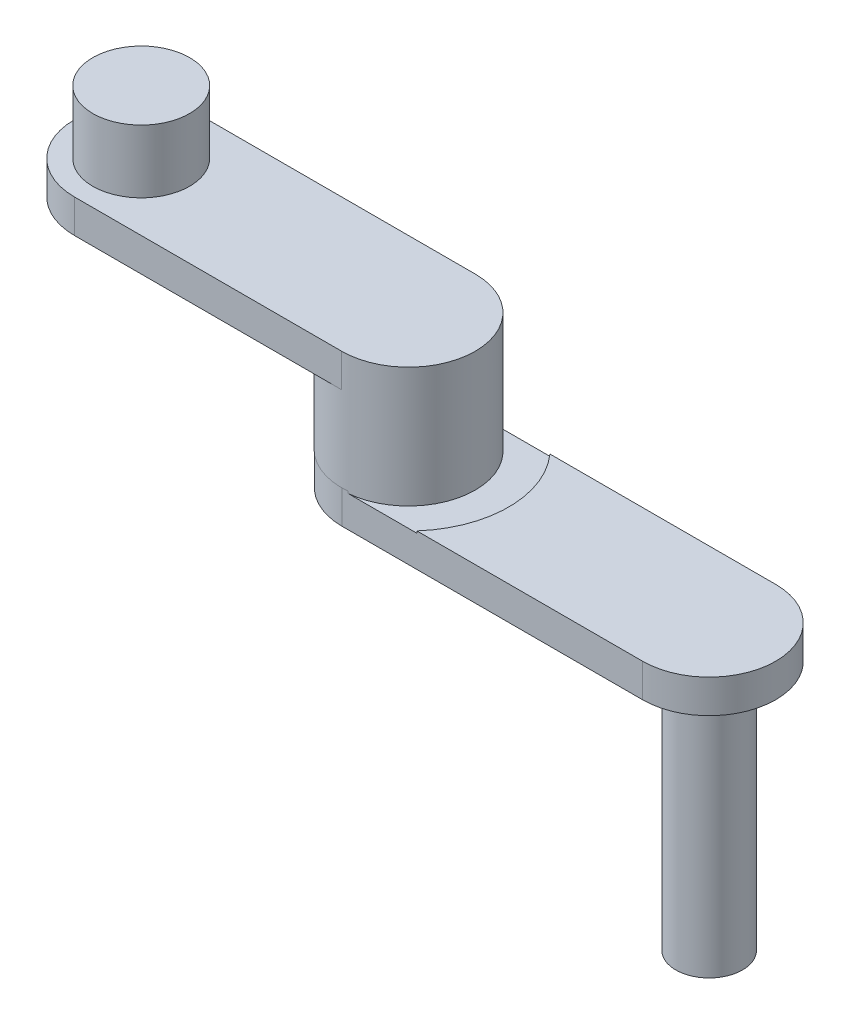
SolidWorks part; units mm, degrees
ref_plane "Front Plane" through (0, 0, 0) normal (0, 0, 1) x (1, 0, 0)
ref_plane "Top Plane" through (0, 0, 0) normal (0, 1, 0) x (1, 0, 0)
ref_plane "Right Plane" through (0, 0, 0) normal (1, 0, 0) x (0, 0, -1)
sketch "Sketch1" plane through (0, 0, 0) normal (0, 1, 0) x (1, 0, 0)
  circle A0 centre (0, 0) radius 30
  dimension "D1" = 60
extrude "Boss-Extrude1" add sketch "Sketch1" along normal blind 25.4 contours A0
sketch "Sketch2" plane through (0, 25.4, 0) normal (0, 1, 0) x (1, 0, 0)
  line L0 (0, 0) -> (-80, 0) construction
  line L1 (0, -20) -> (-80, -20)
  line L2 (0, 20) -> (-80, 20)
  arc A0 (0, -20) -> (0, 20) centre (0, 0) ccw
  arc A1 (-80, 20) -> (-80, -20) centre (-80, 0) ccw
  point P3 (-40, 0)
  dimension "D2" = 20
  dimension "D1" = 80
extrude "Boss-Extrude2" add sketch "Sketch2" along normal blind 10
sketch "Sketch3" plane through (0, 35.4, 0) normal (0, 1, 0) x (1, 0, 0)
  circle A0 centre (-80, 0) radius 14.5
extrude "Boss-Extrude3" add sketch "Sketch3" along normal blind 18.8648
sketch "Sketch4" plane through (0, 0, 0) normal (0, -1, 0) x (1, 0, 0)
  line L0 (0, 0) -> (90, 0) construction
  line L1 (0, 19.9199) -> (90, 19.9199)
  line L2 (0, -19.9199) -> (90, -19.9199)
  arc A0 (0, 19.9199) -> (0, -19.9199) centre (0, 0) ccw
  arc A1 (90, -19.9199) -> (90, 19.9199) centre (90, 0) ccw
  point P3 (45, 0)
extrude "Boss-Extrude4" add sketch "Sketch4" along normal blind 10
sketch "Sketch5" plane through (0, -10, 0) normal (0, -1, 0) x (1, 0, 0)
  circle A0 centre (90, 0) radius 10
extrude "Boss-Extrude5" add sketch "Sketch5" along normal blind 75
sketch "Sketch7" plane through (0, 25.4, 0) normal (0, 1, 0) x (1, 0, 0)
  circle A0 centre (0, 0) radius 20
  circle A1 centre (0, 0) radius 30
extrude "Cut-Extrude1" cut sketch "Sketch7" against normal blind 26
